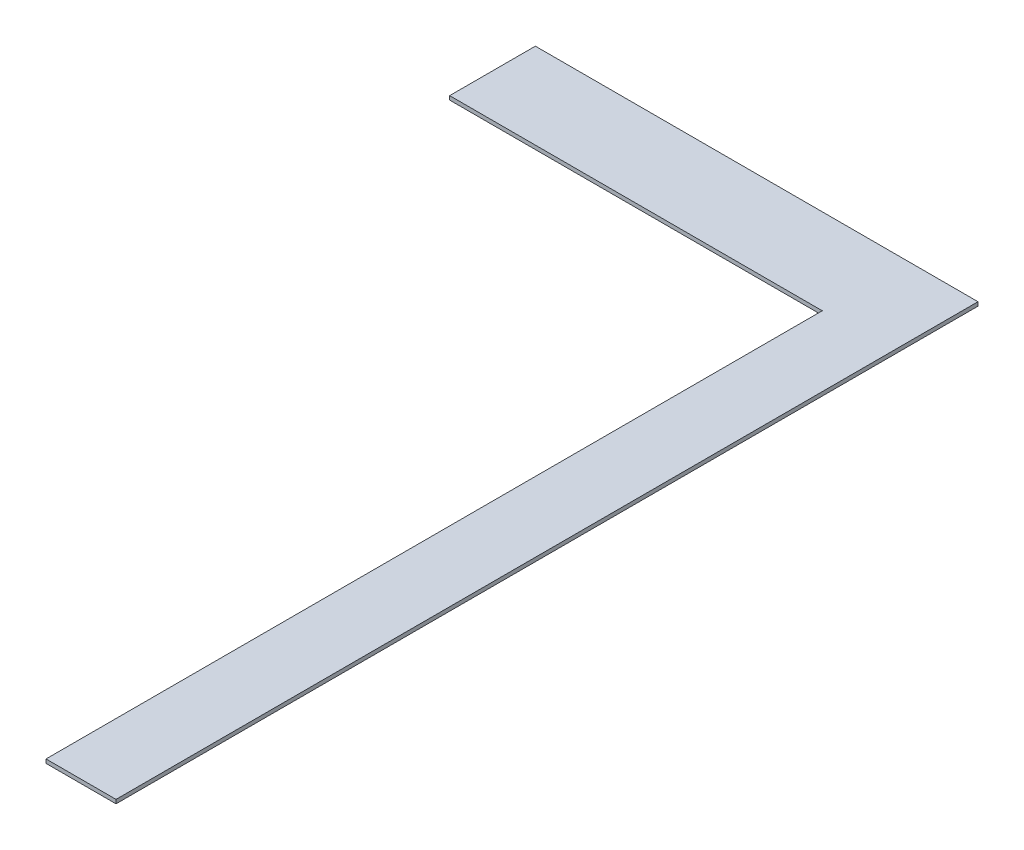
SolidWorks part; units mm, degrees
material "Гипс"
ref_plane "Спереди" through (0, 0, 0) normal (0, 0, 1) x (1, 0, 0)
ref_plane "Сверху" through (0, 0, 0) normal (0, 1, 0) x (1, 0, 0)
ref_plane "Справа" through (0, 0, 0) normal (1, 0, 0) x (0, 0, -1)
sketch "Эскиз1" plane through (0, 0, 0) normal (0, 1, 0) x (1, 0, 0)
  line L0 (-225.5, -276) -> (-225.5, -2776) construction
  line L1 (-1425.5, -276) -> (-225.5, -276) construction
  line L2 (-225.5, -276) -> (-225.5, -2776)
  line L3 (-1425.5, -276) -> (-225.5, -276)
  line L4 (-1425.5, -276) -> (-1425.5, 0)
  line L5 (-1425.5, -1) -> (-1425.5, -376) construction
  line L7 (-1425.5, 0) -> (0, 0)
  line L8 (0, 0) -> (0, -2776)
  line L9 (0, -2776) -> (-225.5, -2776)
extrude "Бобышка-Вытянуть1" add sketch "Эскиз1" against normal blind 12.5
